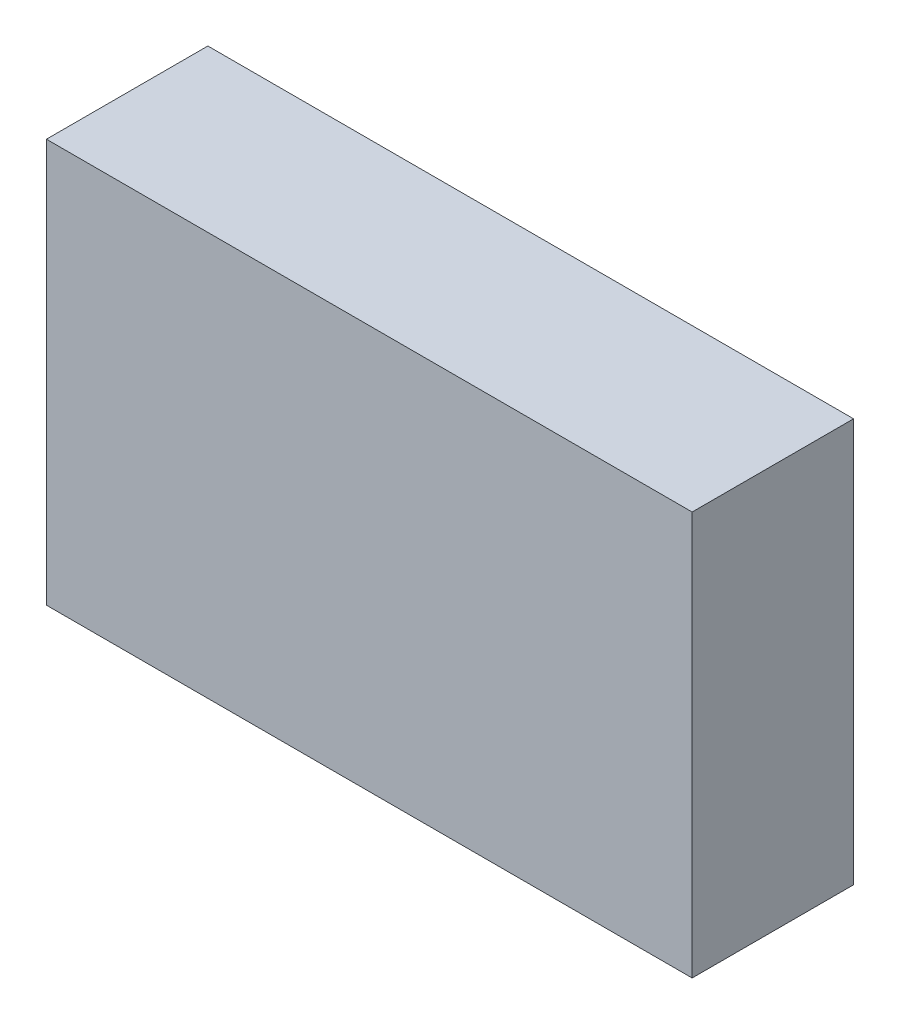
SolidWorks part; units mm, degrees
material "Cedar"
ref_plane "Front Plane" through (0, 0, 0) normal (0, 0, 1) x (1, 0, 0)
ref_plane "Top Plane" through (0, 0, 0) normal (0, 1, 0) x (1, 0, 0)
ref_plane "Right Plane" through (0, 0, 0) normal (1, 0, 0) x (0, 0, -1)
sketch "Sketch1" plane through (0, 0, 0) normal (0, 0, 1) x (1, 0, 0)
  line L0 (20, 10) -> (20, 0) construction
  line L1 (-20, 0) -> (20, 0)
  line L2 (-20, 0) -> (-20, 25)
  line L3 (-20, 25) -> (20, 25)
  line L4 (20, 0) -> (20, 25)
  dimension "D1" = 25
extrude "Boss-Extrude1" add sketch "Sketch1" along normal blind 10 contours L3 L4 L1 L2
